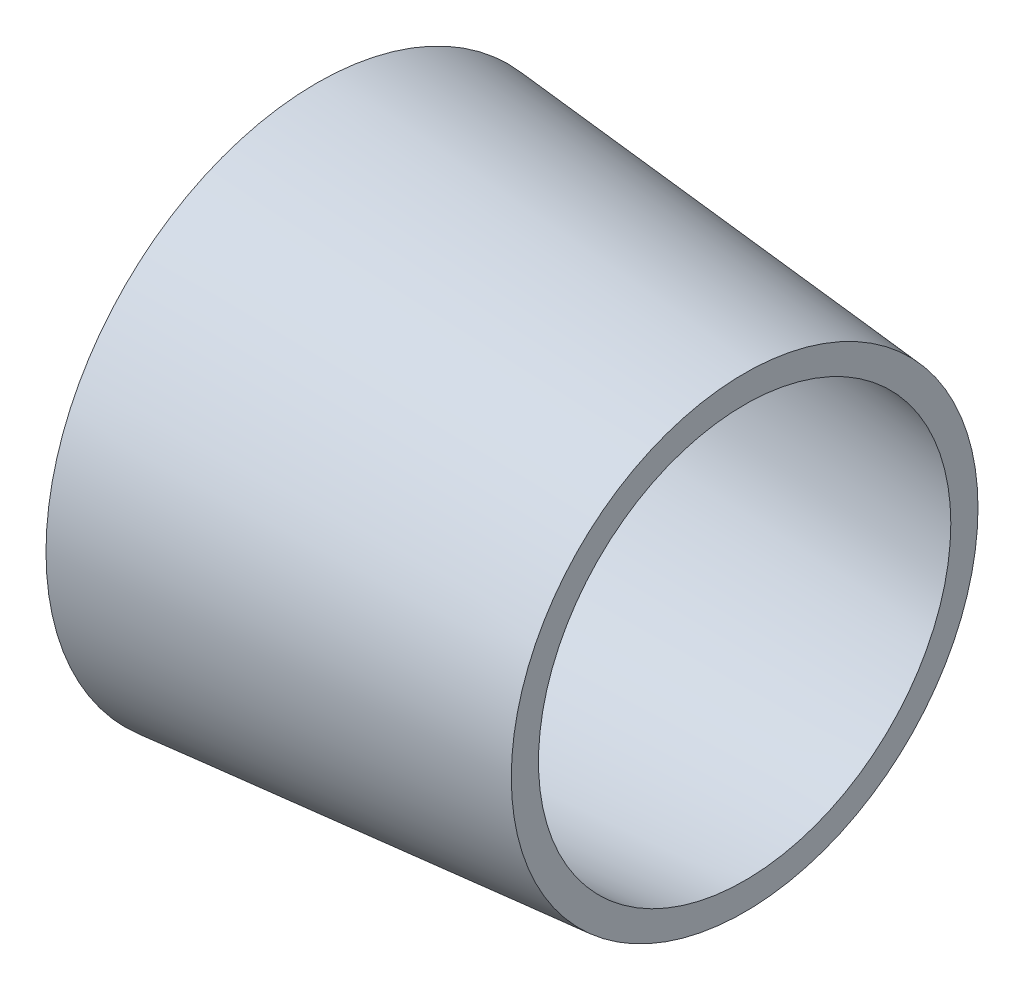
SolidWorks part; units mm, degrees
ref_plane "Front Plane" through (0, 0, 0) normal (0, 0, 1) x (1, 0, 0)
ref_plane "Top Plane" through (0, 0, 0) normal (0, 1, 0) x (1, 0, 0)
ref_plane "Right Plane" through (0, 0, 0) normal (1, 0, 0) x (0, 0, -1)
sketch "Sketch1" plane through (0, 0, 0) normal (1, 0, 0) x (0, 0, -1)
  circle A0 centre (0, 0) radius 25.4
extrude "Boss-Extrude1" add sketch "Sketch1" along normal blind 40.132 draft 5
shell "Shell1" thickness 2.54
scale "Scale1" scale about centroid uniform scaling yes scale factor 18
